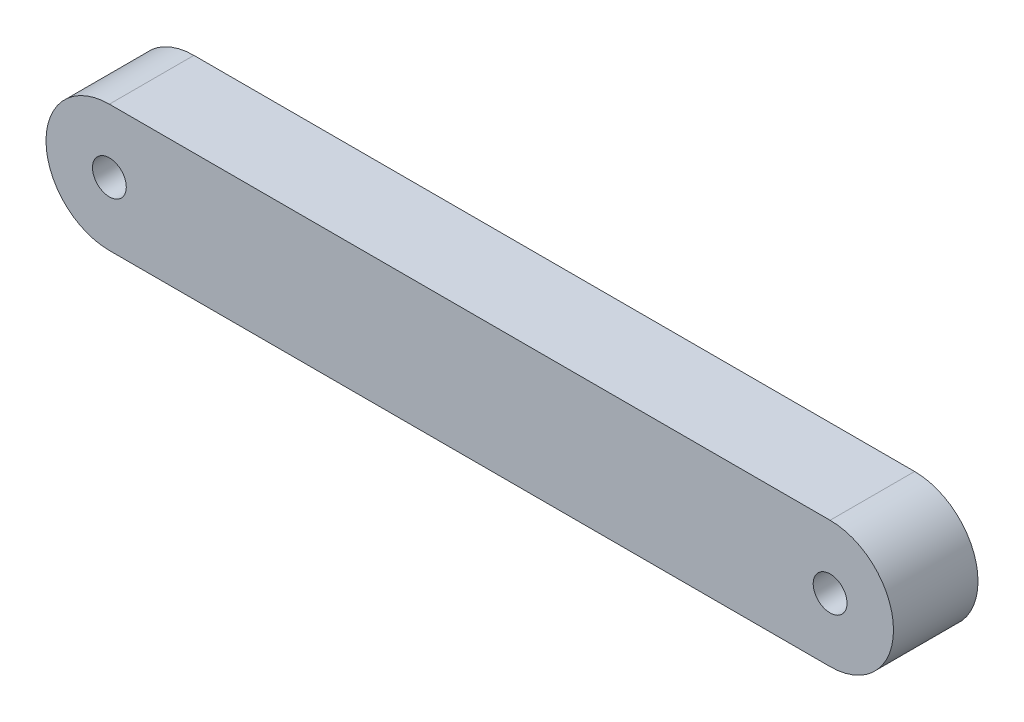
SolidWorks part; units mm, degrees
ref_plane "前视基准面" through (0, 0, 0) normal (0, 0, 1) x (1, 0, 0)
ref_plane "上视基准面" through (0, 0, 0) normal (0, 1, 0) x (1, 0, 0)
ref_plane "右视基准面" through (0, 0, 0) normal (1, 0, 0) x (0, 0, -1)
other "Configuration Table"
sketch "草图1" plane through (0, 0, 0) normal (0, 0, 1) x (1, 0, 0)
  line L0 (0, 15) -> (170.56, 15)
  line L1 (0, -15) -> (170.56, -15)
  arc A0 (0, 15) -> (0, -15) centre (0, 0) ccw
  arc A1 (170.56, -15) -> (170.56, 15) centre (170.56, 0) ccw
  circle A2 centre (0, 0) radius 4
  circle A3 centre (170.56, 0) radius 4
extrude "凸台-拉伸1" add sketch "草图1" along normal blind 20
